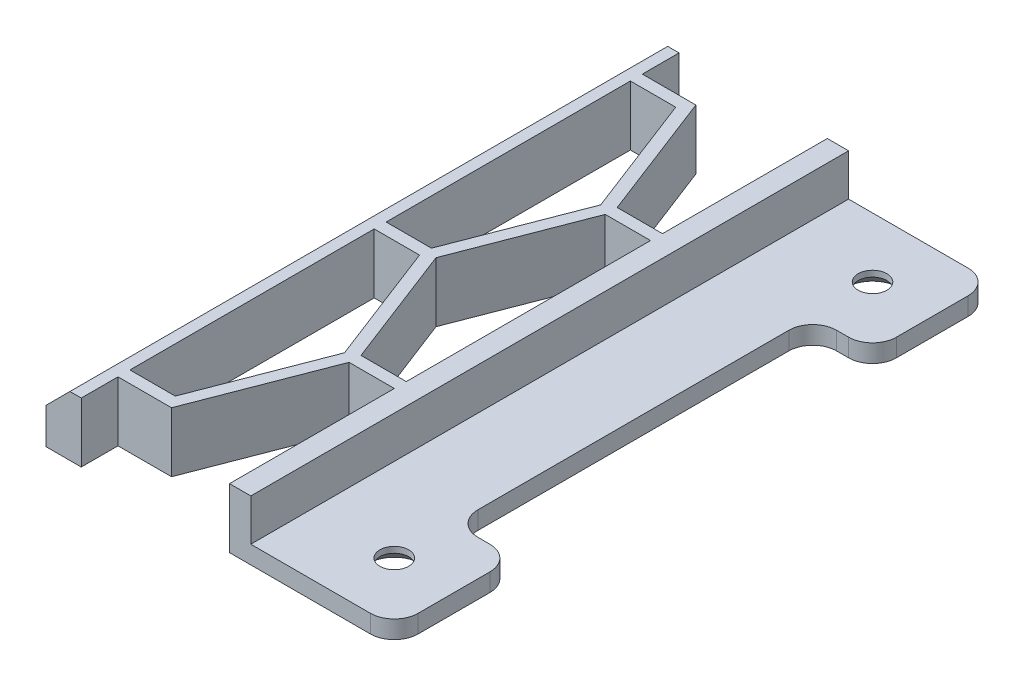
SolidWorks part; units mm, degrees
ref_plane "Front Plane" through (0, 0, 0) normal (0, 0, 1) x (1, 0, 0)
ref_plane "Top Plane" through (0, 0, 0) normal (0, 1, 0) x (1, 0, 0)
ref_plane "Right Plane" through (0, 0, 0) normal (1, 0, 0) x (0, 0, -1)
sketch "Sketch1" plane through (0, 0, 0) normal (0, 1, 0) x (1, 0, 0)
  line L0 (-14.18, 50) -> (-14.18, 46.9286)
  line L1 (-17.13, 50) -> (-14.18, 50)
  line L2 (-17.13, 50) -> (-17.13, 0)
  line L3 (-17.13, 0) -> (-14.18, 0)
  line L5 (-1.78, 50) -> (0, 50)
  line L7 (-1.78, 0) -> (0, 0)
  line L8 (0, 50) -> (0, 0)
  line L9 (-1.78, 50) -> (-1.78, 36.2143)
  line L18 (-14.18, 25) -> (-1.78, 25) construction
  line L20 (-14.18, 25) -> (-10.0467, 25) construction
  line L21 (-10.0467, 25) -> (-5.9133, 35.7143) construction
  line L22 (-5.9133, 35.7143) -> (-1.78, 35.7143) construction
  line L23 (-5.9133, 35.7143) -> (-10.0467, 46.4286) construction
  line L24 (-10.0467, 46.4286) -> (-14.18, 46.4286) construction
  line L25 (-10.0467, 3.5714) -> (-14.18, 3.5714) construction
  line L26 (-5.9133, 14.2857) -> (-10.0467, 3.5714) construction
  line L27 (-5.9133, 14.2857) -> (-1.78, 14.2857) construction
  line L28 (-10.0467, 25) -> (-5.9133, 14.2857) construction
  line L29 (-6.4492, 35.7143) -> (-10.3897, 45.9286)
  line L30 (-10.3897, 45.9286) -> (-14.18, 45.9286)
  line L31 (-5.5703, 36.2143) -> (-1.78, 36.2143)
  line L32 (-10.3897, 25.5) -> (-6.4492, 35.7143)
  line L33 (-14.18, 25.5) -> (-10.3897, 25.5)
  line L34 (-9.5108, 25) -> (-5.5703, 14.7857)
  line L35 (-5.5703, 14.7857) -> (-1.78, 14.7857)
  line L36 (-5.5703, 13.7857) -> (-9.7036, 3.0714)
  line L37 (-9.7036, 3.0714) -> (-14.18, 3.0714)
  line L38 (-5.5703, 36.2143) -> (-9.7036, 46.9286)
  line L39 (-9.7036, 46.9286) -> (-14.18, 46.9286)
  line L40 (-5.5703, 35.2143) -> (-1.78, 35.2143)
  line L41 (-9.5802, 24.82) -> (-5.5703, 35.2143)
  line L42 (-14.18, 24.5) -> (-10.3897, 24.5)
  line L43 (-10.3897, 24.5) -> (-6.4492, 14.2857)
  line L44 (-5.5703, 13.7857) -> (-1.78, 13.7857)
  line L45 (-6.4492, 14.2857) -> (-10.3897, 4.0714)
  line L46 (-10.3897, 4.0714) -> (-14.18, 4.0714)
  line L47 (-14.18, 45.9286) -> (-14.18, 25.5)
  line L48 (-14.18, 24.5) -> (-14.18, 4.0714)
  line L49 (-14.18, 3.0714) -> (-14.18, 0)
  line L50 (-1.78, 35.2143) -> (-1.78, 14.7857)
  line L51 (-1.78, 13.7857) -> (-1.78, 0)
  line L52 (-10.3897, 25.5) -> (-10.0467, 25.5) construction
  line L53 (-5.9133, 36.2143) -> (-5.5703, 36.2143) construction
  line L54 (-5.9133, 36.2143) -> (-1.78, 36.2143) construction
  line L55 (-5.4468, 35.8942) -> (-5.5703, 36.2143) construction
  line L56 (-5.4468, 35.8942) -> (-9.7036, 46.9286) construction
  line L57 (-5.5703, 35.2143) -> (-5.4468, 35.5343) construction
  line L58 (-9.5802, 24.82) -> (-5.4468, 35.5343) construction
  line L59 (-5.9133, 35.2143) -> (-5.5703, 35.2143) construction
  line L60 (-5.9133, 35.2143) -> (-1.78, 35.2143) construction
  line L61 (-6.3798, 35.5343) -> (-6.4492, 35.7143) construction
  line L62 (-6.3798, 35.5343) -> (-10.3897, 45.9286) construction
  line L63 (-6.4492, 35.7143) -> (-6.3798, 35.8942) construction
  line L64 (-10.5132, 25.18) -> (-6.3798, 35.8942) construction
  line L65 (-9.5802, 25.18) -> (-9.5108, 25) construction
  line L66 (-9.5802, 25.18) -> (-5.4468, 14.4657) construction
  line L67 (-14.18, 25.5) -> (-10.0467, 25.5) construction
  line L68 (-10.5132, 25.18) -> (-10.3897, 25.5) construction
  line L69 (-10.5132, 24.82) -> (-10.3897, 24.5) construction
  line L70 (-10.5132, 24.82) -> (-6.3798, 14.1058) construction
  line L71 (-10.3897, 24.5) -> (-10.0467, 24.5) construction
  line L72 (-14.18, 24.5) -> (-10.0467, 24.5) construction
  line L73 (-5.9133, 14.7857) -> (-5.5703, 14.7857) construction
  line L74 (-5.9133, 14.7857) -> (-1.78, 14.7857) construction
  line L75 (-5.5703, 14.7857) -> (-5.4468, 14.4657) construction
  line L76 (-5.4468, 14.1058) -> (-5.5703, 13.7857) construction
  line L77 (-5.4468, 14.1058) -> (-9.7036, 3.0714) construction
  line L78 (-5.9133, 13.7857) -> (-5.5703, 13.7857) construction
  line L79 (-5.9133, 13.7857) -> (-1.78, 13.7857) construction
  line L80 (-6.4492, 14.2857) -> (-6.3798, 14.1058) construction
  line L81 (-6.3798, 14.4657) -> (-6.4492, 14.2857) construction
  line L82 (-6.3798, 14.4657) -> (-10.3897, 4.0714) construction
  dimension "D2" = 12.4
  dimension "D4" = 4.1333
  dimension "D5" = 4.1333
  dimension "D7" = 14.2857
  dimension "D1" = 50
  dimension "D3" = 2.95
  dimension "D10" = 25
  dimension "D11" = 25
  dimension "D6" = 1.78
  dimension "D8" = 0.5
  dimension "D9" = 0.5
extrude "Boss-Extrude1" add sketch "Sketch1" along normal blind 5
sketch "Sketch5" plane through (0, 0, 0) normal (0, -1, 0) x (1, 0, 0)
  line L0 (12, -40) -> (12, -50)
  line L1 (0, 0) -> (12, 0)
  line L2 (0, 0) -> (0, -50)
  line L3 (0, -50) -> (12, -50)
  line L4 (12, 0) -> (12, -10)
  line L5 (12, -10) -> (7, -10)
  line L7 (12, -40) -> (7, -40)
  line L8 (7, -10) -> (7, -40)
  circle A0 centre (7, -5) radius 1.1 construction
  circle A1 centre (7, -45) radius 1.1 construction
  point P9 (7, -25)
  point P10 (0, -25)
  point P17 (12, -5)
  point P19 (12, -45)
  dimension "D4" = 2.2
  dimension "D1" = 30
  dimension "D2" = 12
  dimension "D3" = 5
extrude "Boss-Extrude3" add sketch "Sketch5" against normal blind 1.5
fillet "Fillet1" radius 2 6 edges at (12, 0.75, -10) (7, 0.75, -10) (7, 0.75, -40) (12, 0.75, -40) (12, 0.75, -50) (12, 0.75, 0)
hole_wizard "CSK for M2 Flat Head Machine Screw1" positions "3DSketch1" profile "Sketch6" countersink size "M2" standard "ANSI Metric" end condition up to next
sketch3d "3DSketch1"
  point P0 (7, 0, -5)
  point P3 (7, 0, -45)
sketch "Sketch6" plane through (7, 0, -5) normal (1, 0, 0) x (0, 0, -1)
  line L0 (0, 0) -> (0, 1.5)
  line L1 (0, 1.5) -> (1.2, 1.5)
  line L2 (1.2, 1.5) -> (1.2, 1)
  line L3 (1.2, 1) -> (2.2, 0)
  line L5 (2.2, 0) -> (0, 0)
  line L6 (-1.2, 1) -> (-2.2, 0) construction
  line L11 (0, -6.35) -> (0, 107.95) construction
  dimension "Thru Hole Dia." = 2.4
  dimension "Thru Hole Depth" = 1.5
  dimension "Near C'Sink Dia." = 4.4
  dimension "Near C'Sink Angle" = 90
chamfer "Chamfer1" distance 2 angle 45 1 edges at (-17.13, 5, -25)
equation "\"bracket-length\"= 50"
equation "\"gap\"= 15 - 2.6"
equation "\"D4@Sketch1\"=\"gap\"/3"
equation "\"D5@Sketch1\"=\"gap\"/3"
equation "\"D2@Sketch1\"=\"gap\""
equation "\"D7@Sketch1\"=\"bracket-length\"/3.5"
equation "\"D1@Sketch1\"=\"bracket-length\""
equation "\"D10@Sketch1\"=\"bracket-length\"/2"
